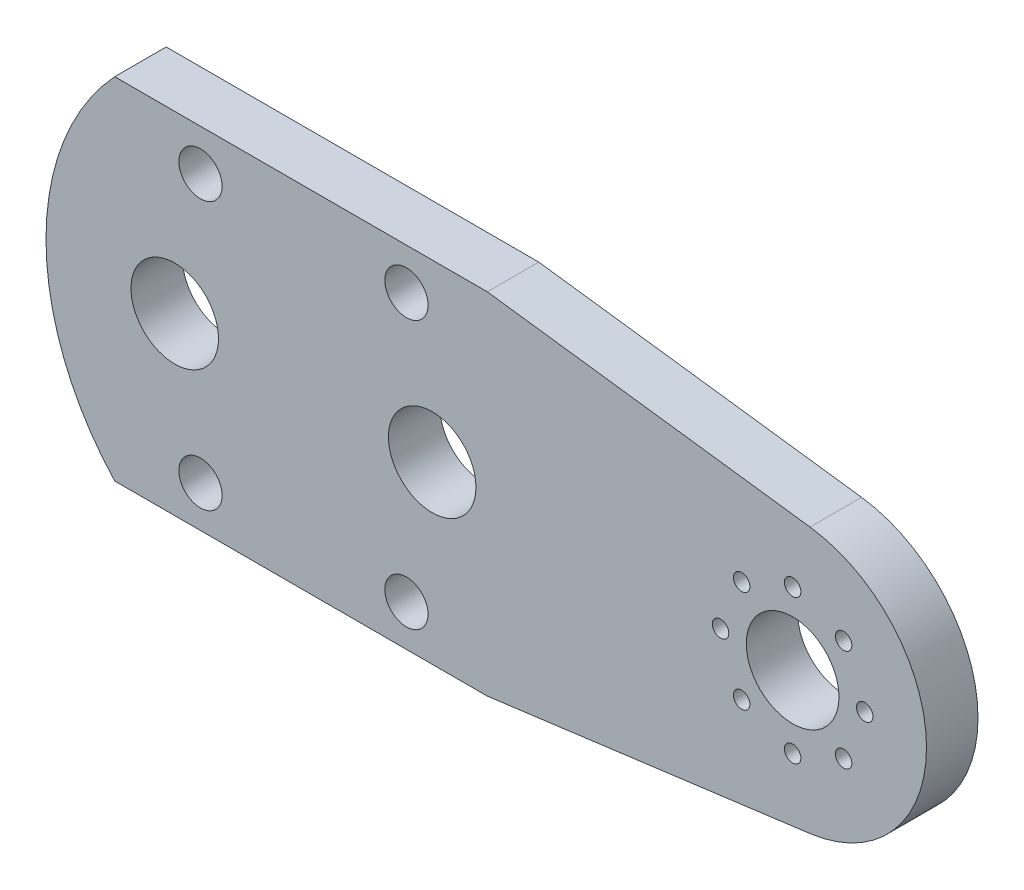
SolidWorks part; units mm, degrees
ref_plane "Front Plane" through (0, 0, 0) normal (0, 0, 1) x (1, 0, 0)
ref_plane "Top Plane" through (0, 0, 0) normal (0, 1, 0) x (1, 0, 0)
ref_plane "Right Plane" through (0, 0, 0) normal (1, 0, 0) x (0, 0, -1)
sketch "Sketch1" plane through (0, 0, 0) normal (0, 0, 1) x (1, 0, 0)
  line L0 (-25, 0) -> (0, 0) construction
  line L1 (-12.5, 0) -> (-12.5, -11.0721) construction
  line L2 (-12.5, 0) -> (-12.5, 17) construction
  line L3 (-30.8303, 17) -> (5.3536, 17)
  line L4 (-30.8303, -17) -> (5.3536, -17)
  line L7 (5.3536, 17) -> (36.6907, 12.8896)
  line L8 (5.3536, -17) -> (36.6907, -12.8896)
  circle A0 centre (0, 0) radius 4.25
  circle A1 centre (-25, 0) radius 4.25
  circle A2 centre (-22.5, -13) radius 2.1
  circle A3 centre (-2.5, -13) radius 2.1
  circle A4 centre (-2.5, 13) radius 2.1
  circle A5 centre (-22.5, 13) radius 2.1
  arc A6 (-30.8303, 17) -> (-30.8303, -17) centre (-12.5, 0) ccw
  arc A28 (36.6907, -12.8896) -> (36.6907, 12.8896) centre (35, 0) ccw
  point P4 (-12.5, 0)
  arc B0 (25.5, 0) -> (44.5, 0) centre (35, 0) ccw
  arc B1 (44.5, 0) -> (25.5, 0) centre (35, 0) ccw
  arc B2 (30.5, 0) -> (39.5, 0) centre (35, 0) ccw
  arc B3 (39.5, 0) -> (30.5, 0) centre (35, 0) ccw
  arc B4 (30.8503, 4.9497) -> (29.2503, 4.9497) centre (30.0503, 4.9497) ccw
  arc B5 (29.2503, 4.9497) -> (30.8503, 4.9497) centre (30.0503, 4.9497) ccw
  arc B6 (28.8, 0) -> (27.2, 0) centre (28, 0) ccw
  arc B7 (27.2, 0) -> (28.8, 0) centre (28, 0) ccw
  arc B8 (30.8503, -4.9497) -> (29.2503, -4.9497) centre (30.0503, -4.9497) ccw
  arc B9 (29.2503, -4.9497) -> (30.8503, -4.9497) centre (30.0503, -4.9497) ccw
  arc B10 (34.2, -7) -> (35.8, -7) centre (35, -7) ccw
  arc B11 (35.8, -7) -> (34.2, -7) centre (35, -7) ccw
  arc B12 (39.1497, -4.9497) -> (40.7497, -4.9497) centre (39.9497, -4.9497) ccw
  arc B13 (40.7497, -4.9497) -> (39.1497, -4.9497) centre (39.9497, -4.9497) ccw
  arc B14 (41.2, 0) -> (42.8, 0) centre (42, 0) ccw
  arc B15 (42.8, 0) -> (41.2, 0) centre (42, 0) ccw
  arc B16 (39.1497, 4.9497) -> (40.7497, 4.9497) centre (39.9497, 4.9497) ccw
  arc B17 (40.7497, 4.9497) -> (39.1497, 4.9497) centre (39.9497, 4.9497) ccw
  arc B18 (35.8, 7) -> (34.2, 7) centre (35, 7) ccw
  arc B19 (34.2, 7) -> (35.8, 7) centre (35, 7) ccw
  dimension "D1" = 8.5
  dimension "D2" = 8.5
  dimension "D3" = 25
  dimension "D4" = 2.5
  dimension "D5" = 13
  dimension "D6" = 4.2
  dimension "D7" = 50
  dimension "D9" = 26
  dimension "D8" = 17
  dimension "D10" = 35
sketch_block_instance "Block1-1"
sketch_block "Block1"
extrude "Boss-Extrude1" add sketch "Sketch1" along normal blind 5 contours L8 A28 L7 L3 A6 L4 B1 B0 A5 A4 A0 A1 A2 A3 | B0 B1 B19 B18 B17 B16 B15 B14 B13 B12 B11 B10 B9 B8 B7 B6 B5 B4 B3 B2
move or copy body "Body-Move/Copy1" [suppressed] bodies to move or copy 101
